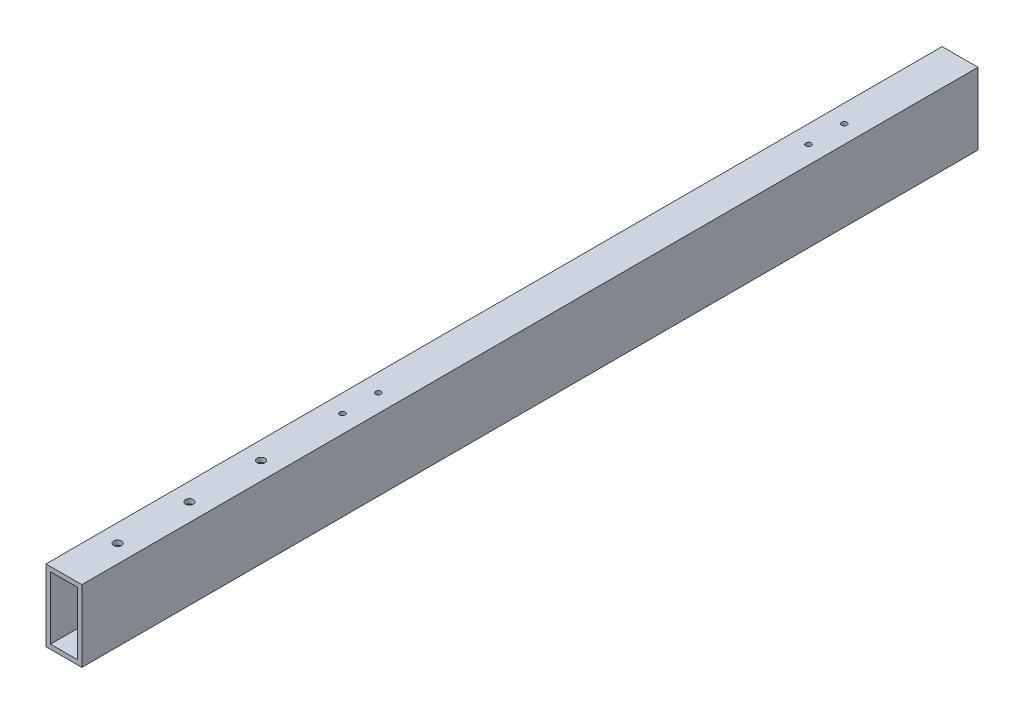
SolidWorks part; units mm, degrees
material "6061-T4 (SS)"
ref_plane "Front Plane" through (0, 0, 0) normal (0, 0, 1) x (1, 0, 0)
ref_plane "Top Plane" through (0, 0, 0) normal (0, 1, 0) x (1, 0, 0)
ref_plane "Right Plane" through (0, 0, 0) normal (1, 0, 0) x (0, 0, -1)
sketch "Sketch1" plane through (0, 0, 0) normal (0, 0, 1) x (1, 0, 0)
  line L0 (-9.525, 22.225) -> (9.525, 22.225)
  line L1 (-12.7, 25.4) -> (12.7, 25.4)
  line L2 (-12.7, 25.4) -> (-12.7, -25.4)
  line L3 (-12.7, -25.4) -> (12.7, -25.4)
  line L4 (12.7, 25.4) -> (12.7, -25.4)
  line L5 (-12.7, 25.4) -> (12.7, -25.4) construction
  line L6 (-12.7, -25.4) -> (12.7, 25.4) construction
  line L7 (9.525, 22.225) -> (9.525, -22.225)
  line L8 (-9.525, -22.225) -> (9.525, -22.225)
  line L9 (-9.525, 22.225) -> (-9.525, -22.225)
  point P0 (0, 0)
  dimension "D1" = 50.8
  dimension "D2" = 25.4
  dimension "D3" = 3.175
extrude "Boss-Extrude1" add sketch "Sketch1" along normal mid plane 635
sketch "Sketch2" plane through (0, 25.4, 0) normal (0, 1, 0) x (1, 0, 0)
  line L0 (12.7, -317.5) -> (-12.7, -317.5) construction
  line L1 (-12.7, -317.5) -> (-12.7, 317.5) construction
  line L2 (12.7, 317.5) -> (-12.7, 317.5) construction
  line L3 (12.7, -317.5) -> (12.7, 317.5) construction
  circle A0 centre (0, -120.1166) radius 1.905
  circle A1 centre (0, -94.7166) radius 1.905
  circle A2 centre (0, 235.4859) radius 1.905
  circle A3 centre (0, 210.0859) radius 1.905
  dimension "D1" = 3.81
  dimension "D2" = 197.3834
  dimension "D3" = 12.7
  dimension "D4" = 25.4
  dimension "D5" = 12.7
  dimension "D6" = 82.0141
  dimension "D7" = 12.7
  dimension "D8" = 25.4
extrude "Cut-Extrude1" cut sketch "Sketch2" against normal through all
sketch "Sketch3" plane through (0, 25.4, 0) normal (0, 1, 0) x (1, 0, 0)
  line L1 (12.7, -317.5) -> (12.7, 317.5) construction
  circle A0 centre (673.1, -279.3999) radius 2.1971
  circle A1 centre (673.1, -228.5999) radius 2.1971
  circle A2 centre (673.1, -177.7999) radius 2.1971
  circle A3 centre (673.1, -228.5999) radius 2.5527 construction
  circle A4 centre (0, -279.3999) radius 2.8067
  circle A5 centre (0, -228.5999) radius 2.8067
  circle A6 centre (0, -177.7999) radius 2.8067
  dimension "D1" = 4.3942
  dimension "D2" = 5.6134
  dimension "D3" = 50.8
  dimension "D4" = 12.7
extrude "Cut-Extrude2" cut sketch "Sketch3" against normal through all
